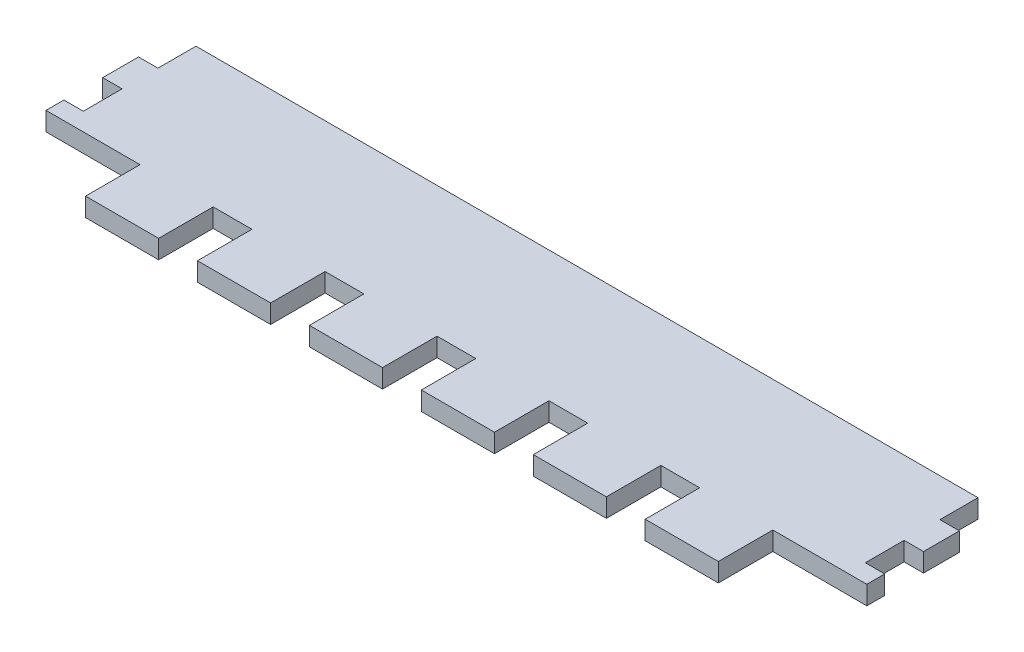
SolidWorks part; units mm, degrees
ref_plane "Front Plane" through (0, 0, 0) normal (0, 0, 1) x (1, 0, 0)
ref_plane "Top Plane" through (0, 0, 0) normal (0, 1, 0) x (1, 0, 0)
ref_plane "Right Plane" through (0, 0, 0) normal (1, 0, 0) x (0, 0, -1)
sketch "Sketch1" plane through (0, 0, 0) normal (0, 1, 0) x (1, 0, 0)
  line L2 (-139.7, -28.575) -> (-139.7, 28.575)
  line L3 (-139.7, 28.575) -> (139.7, 28.575)
  line L4 (139.7, -28.575) -> (139.7, 28.575)
  line L5 (-139.7, -28.575) -> (139.7, 28.575) construction
  line L6 (-139.7, 28.575) -> (139.7, -28.575) construction
  line L11 (-139.7, -28.575) -> (139.7, -28.575)
  point P0 (0, 0)
  dimension "D1" = 57.15
  dimension "D2" = 279.4
extrude "Boss-Extrude1" add sketch "Sketch1" along normal blind 6.35
sketch "Sketch3" plane through (0, 0, 0) normal (0, 1, 0) x (1, 0, 0)
  line L0 (-139.7, -28.575) -> (139.7, -28.575) construction
  line L1 (-107.696, -28.575) -> (-107.696, -47.117)
  line L2 (-107.696, -47.117) -> (-82.804, -47.117)
  line L3 (-82.804, -47.117) -> (-82.804, -28.575)
  line L4 (-82.804, -28.575) -> (-107.696, -28.575)
  line L5 (-69.596, -28.575) -> (-69.596, -47.117)
  line L6 (-69.596, -47.117) -> (-44.704, -47.117)
  line L7 (-44.704, -47.117) -> (-44.704, -28.575)
  line L8 (-44.704, -28.575) -> (-69.596, -28.575)
  line L9 (-31.496, -28.575) -> (-31.496, -47.117)
  line L10 (-31.496, -47.117) -> (-6.604, -47.117)
  line L11 (-6.604, -47.117) -> (-6.604, -28.575)
  line L12 (-6.604, -28.575) -> (-31.496, -28.575)
  line L13 (6.604, -28.575) -> (6.604, -47.117)
  line L14 (6.604, -47.117) -> (31.496, -47.117)
  line L15 (31.496, -47.117) -> (31.496, -28.575)
  line L16 (31.496, -28.575) -> (6.604, -28.575)
  line L17 (44.704, -28.575) -> (44.704, -47.117)
  line L18 (44.704, -47.117) -> (69.596, -47.117)
  line L19 (69.596, -47.117) -> (69.596, -28.575)
  line L20 (69.596, -28.575) -> (44.704, -28.575)
  line L21 (82.804, -28.575) -> (82.804, -47.117)
  line L22 (82.804, -47.117) -> (107.696, -47.117)
  line L23 (107.696, -47.117) -> (107.696, -28.575)
  line L24 (107.696, -28.575) -> (82.804, -28.575)
  point P0 (-95.25, -28.575)
  point P6 (-57.15, -28.575)
  point P14 (-19.05, -28.575)
  point P19 (19.05, -28.575)
  point P24 (57.15, -28.575)
  point P29 (95.25, -28.575)
  dimension "D1" = 24.892
  dimension "D2" = 18.542
  dimension "D3" = 44.45
extrude "Boss-Extrude2" add sketch "Sketch3" along normal blind 6.35
sketch "Sketch4" plane through (0, 0, 0) normal (0, 1, 0) x (1, 0, 0)
  line L0 (-139.7, 28.575) -> (-139.7, -28.575) construction
  line L1 (139.7, 28.575) -> (-139.7, 28.575) construction
  line L2 (-146.304, 16.129) -> (-133.096, 16.129)
  line L3 (-146.304, 16.129) -> (-146.304, 2.921)
  line L4 (-146.304, 2.921) -> (-133.096, 2.921)
  line L5 (-133.096, 16.129) -> (-133.096, 2.921)
  line L6 (-146.304, 16.129) -> (-133.096, 2.921) construction
  line L7 (-146.304, 2.921) -> (-133.096, 16.129) construction
  line L8 (0, 0) -> (0, 63.6475) construction
  line L9 (-146.304, -9.271) -> (-133.096, -9.271)
  line L10 (-133.096, -9.271) -> (-133.096, -22.479)
  line L11 (-146.304, -22.479) -> (-133.096, -22.479)
  line L12 (-146.304, -9.271) -> (-146.304, -22.479)
  line L13 (146.304, 2.921) -> (133.096, 16.129) construction
  line L14 (146.304, 16.129) -> (133.096, 2.921) construction
  line L15 (146.304, -9.271) -> (146.304, -22.479)
  line L16 (146.304, -22.479) -> (133.096, -22.479)
  line L17 (133.096, -9.271) -> (133.096, -22.479)
  line L18 (146.304, -9.271) -> (133.096, -9.271)
  line L19 (133.096, 16.129) -> (133.096, 2.921)
  line L20 (146.304, 2.921) -> (133.096, 2.921)
  line L21 (146.304, 16.129) -> (146.304, 2.921)
  line L22 (146.304, 16.129) -> (133.096, 16.129)
  point P0 (-139.7, 9.525)
  point P1 (-139.7, 9.525)
  point P25 (139.7, 9.525)
  dimension "D1" = 13.208
  dimension "D2" = 13.208
  dimension "D3" = 19.05
  dimension "D5" = 2
extrude "Cut-Extrude2" cut sketch "Sketch4" along normal through all
sketch "Sketch5" plane through (0, 6.35, 0) normal (0, 1, 0) x (1, 0, 0)
  line L1 (-139.7, 28.575) -> (171.8176, 28.575)
  line L2 (-139.7, 28.575) -> (-139.7, 15.875)
  line L3 (-139.7, 15.875) -> (171.8176, 15.875)
  line L4 (171.8176, 28.575) -> (171.8176, 15.875)
  dimension "D1" = 12.7
extrude "Cut-Extrude3" cut sketch "Sketch5" against normal through all
